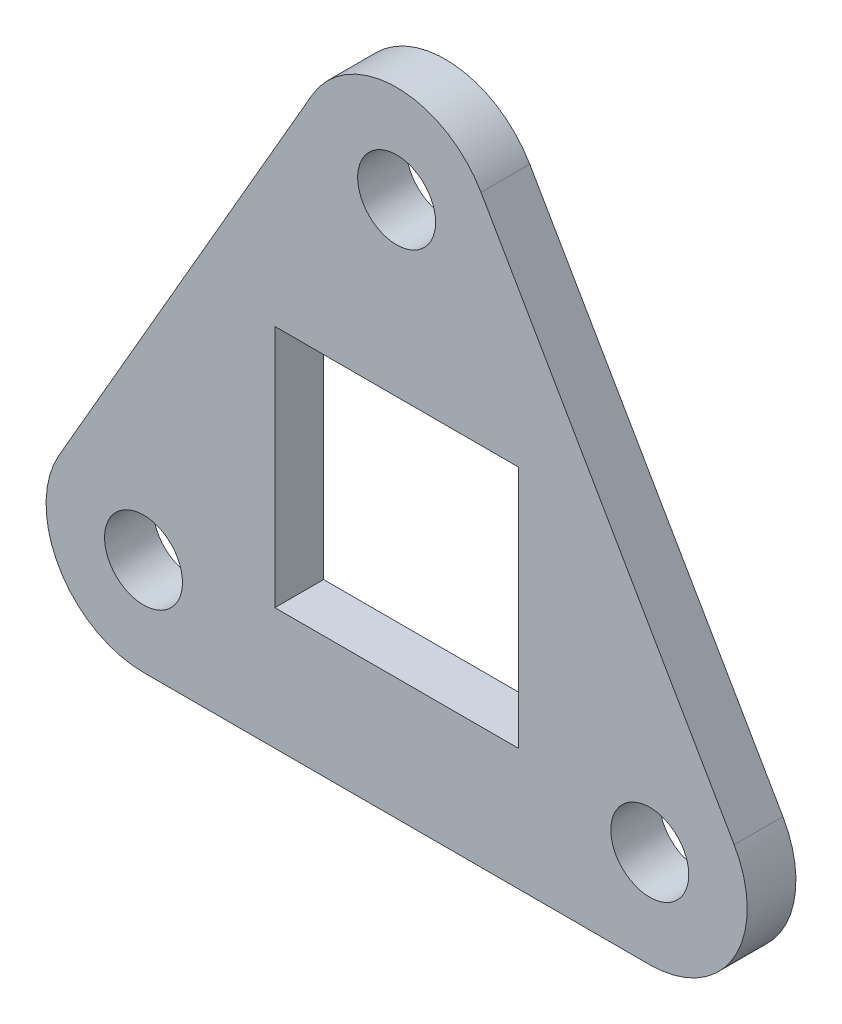
SolidWorks part; units mm, degrees
material "ﾎﾟﾘｶｰﾎﾞﾈｰﾄ(PC)高粘度"
ref_plane "正面" through (0, 0, 0) normal (0, 0, 1) x (1, 0, 0)
ref_plane "平面" through (0, 0, 0) normal (0, 1, 0) x (1, 0, 0)
ref_plane "右側面" through (0, 0, 0) normal (1, 0, 0) x (0, 0, -1)
sketch "ｽｹｯﾁ1" plane through (0, 0, 0) normal (0, 0, 1) x (1, 0, 0)
  line L0 (0, 0) -> (0, 12) construction
  line L1 (5, -5) -> (-5, -5)
  line L2 (5, -5) -> (5, 5)
  line L3 (5, 5) -> (-5, 5)
  line L4 (-5, -5) -> (-5, 5)
  line L5 (5, -5) -> (-5, 5) construction
  line L6 (5, 5) -> (-5, -5) construction
  line L7 (0, 0) -> (10.3923, -6) construction
  line L8 (0, 0) -> (-10.3923, -6) construction
  line L9 (-13.8564, -4) -> (-3.4641, 14)
  line L10 (-10.3923, -10) -> (10.3923, -10)
  line L11 (3.4641, 14) -> (13.8564, -4)
  circle A0 centre (0, 12) radius 1.6
  circle A1 centre (10.3923, -6) radius 1.6
  circle A2 centre (-10.3923, -6) radius 1.6
  arc A3 (-3.4641, 14) -> (3.4641, 14) centre (0, 12) cw
  arc A4 (-13.8564, -4) -> (-10.3923, -10) centre (-10.3923, -6) ccw
  arc A5 (10.3923, -10) -> (13.8564, -4) centre (10.3923, -6) ccw
  point P0 (0, 0)
  point P15 (0, 0)
  dimension "D1" = 3.2
  dimension "D5" = 4
  dimension "D2" = 10
  dimension "D3" = 12
  dimension "D4" = 3
extrude "ﾎﾞｽ - 押し出し1" add sketch "ｽｹｯﾁ1" along normal blind 2
